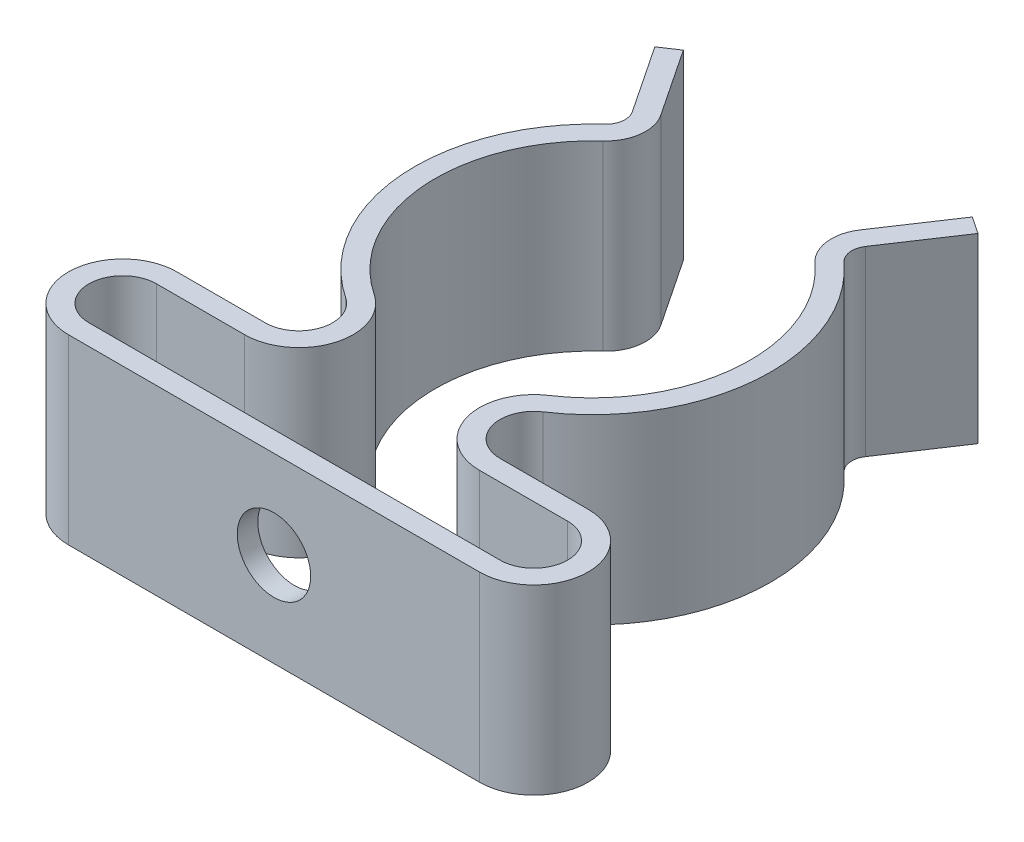
SolidWorks part; units mm, degrees
ref_plane "Front Plane" through (0, 0, 0) normal (0, 0, 1) x (1, 0, 0)
ref_plane "Top Plane" through (0, 0, 0) normal (0, 1, 0) x (1, 0, 0)
ref_plane "Right Plane" through (0, 0, 0) normal (1, 0, 0) x (0, 0, -1)
sketch "Sketch1" plane through (0, 0, 0) normal (0, 1, 0) x (1, 0, 0)
  line L0 (-7, 0) -> (7, 0)
  line L1 (7, 3) -> (4, 3)
  line L2 (3.6811, 16.0216) -> (5.2111, 18.3167)
  line L3 (0, 18.3167) -> (0, 0) construction
  line L4 (-3.6811, 16.0216) -> (-5.2111, 18.3167)
  line L5 (-7, 3) -> (-4, 3)
  arc A0 (7, 0) -> (7, 3) centre (7, 1.5) ccw
  arc A1 (4, 3) -> (3.1679, 5.7481) centre (4, 4.5) cw
  arc A2 (3.1679, 5.7481) -> (3.8407, 14.7268) centre (0, 10.5) ccw
  arc A3 (3.8407, 14.7268) -> (3.6811, 16.0216) centre (4.5131, 15.4669) cw
  arc A4 (-3.8407, 14.7268) -> (-3.6811, 16.0216) centre (-4.5131, 15.4669) ccw
  arc A5 (-3.1679, 5.7481) -> (-3.8407, 14.7268) centre (0, 10.5) cw
  arc A6 (-4, 3) -> (-3.1679, 5.7481) centre (-4, 4.5) ccw
  arc A7 (-7, 0) -> (-7, 3) centre (-7, 1.5) cw
  point P3 (7, 1.5)
  point P6 (4, 4.5)
  point P10 (0, 10.5)
  dimension "D6" = 1
  dimension "D1" = 7
  dimension "D2" = 1.5
  dimension "D3" = 3
  dimension "D4" = 1.5
  dimension "D5" = 10.5
extrude "Extrude-Thin3" add sketch "Sketch1" along normal blind 6 and the other way blind 0.2 thin thin type mid plane wall 0.7
sketch "Sketch2" plane through (0, 0, 0.35) normal (0, 0, 1) x (1, 0, 0)
  line L0 (7, 6) -> (-7, 6) construction
  line L1 (7, -0.2) -> (7, 6) construction
  circle A0 centre (0, 3) radius 1.25
  point P0 (0, 3)
  dimension "D1" = 3
  dimension "D2" = 7
extrude "Extrude1" cut sketch "Sketch2" against normal up to next
